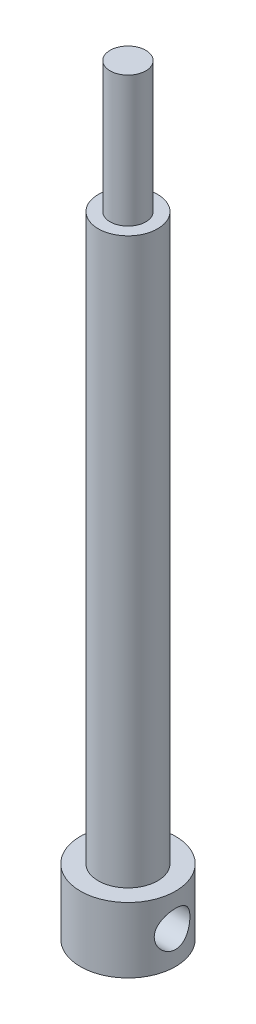
SolidWorks part; units mm, degrees
ref_plane "Piano frontale" through (0, 0, 0) normal (0, 0, 1) x (1, 0, 0)
ref_plane "Piano superiore" through (0, 0, 0) normal (0, 1, 0) x (1, 0, 0)
ref_plane "Piano destro" through (0, 0, 0) normal (1, 0, 0) x (0, 0, -1)
sketch "Schizzo1" plane through (0, 0, 0) normal (0, 1, 0) x (1, 0, 0)
  circle A0 centre (0, 0) radius 8
  dimension "D1" = 16
extrude "Estrusione-Estrusione1" add sketch "Schizzo1" along normal blind 128
sketch "Schizzo2" plane through (0, 128, 0) normal (0, 1, 0) x (1, 0, 0)
  circle A0 centre (0, 0) radius 3
  circle A1 centre (0, 0) radius 8 construction
  circle A2 centre (0, 0) radius 8
  dimension "D1" = 6
extrude "Taglio-Estrusione1" cut sketch "Schizzo2" against normal blind 22
sketch "Schizzo5" plane through (0, 106, 0) normal (0, 1, 0) x (1, 0, 0)
  circle A0 centre (0, 0) radius 8 construction
  circle A1 centre (0, 0) radius 8
  circle A2 centre (0, 0) radius 5
  dimension "D1" = 10
extrude "Taglio-Estrusione2" cut sketch "Schizzo5" against normal offset from surface (95 mm away) 11 up to face at (0, 0, 8)
cosmetic thread "Filettatura cosmetica1" parameters "D1"=95, "D2"=8.344
sketch "Schizzo9" plane through (0, 0, 0) normal (1, 0, 0) x (0, 0, -1)
  line L6 (-8, 0) -> (8, 0) construction
  circle A0 centre (0, 5.5) radius 3
  point P2 (0, 0)
  point P3 (0, 0)
  point P5 (0, 0)
  dimension "D1" = 6
  dimension "D2" = 5.5
extrude "Taglio-Estrusione3" cut sketch "Schizzo9" against normal through all both and the other way through all
thread "Filettatura1" pitch 1 start angle 0, offset 0, length 95, pitch 1, diameter 10
ref_plane "Piano2" through (-5, 106, 0) normal (0, 0, 1) x (-1, 0, 0)
sketch "Profilo filettatura2" plane through (-5, 106, 0) normal (0, 0, 1) x (-1, 0, 0)
  line L0 (0, 0) -> (0, 1) construction
  line L11 (0, 0) -> (0, 0.875)
  line L12 (0, 0.875) -> (-0.5413, 0.5625)
  line L13 (-0.5413, 0.5625) -> (-0.5413, 0.3125)
  line L15 (-0.5413, 0.3125) -> (0, 0)
  line L17 (-0.5413, 0.4375) -> (0, 0.4375) construction
  point P2 (0, 0)
  dimension "Pitch" = 1
  dimension "Profile_Angle" = 60
  dimension "Profile_Land" = 0.25
  dimension "Profile_Height" = 0.5413
